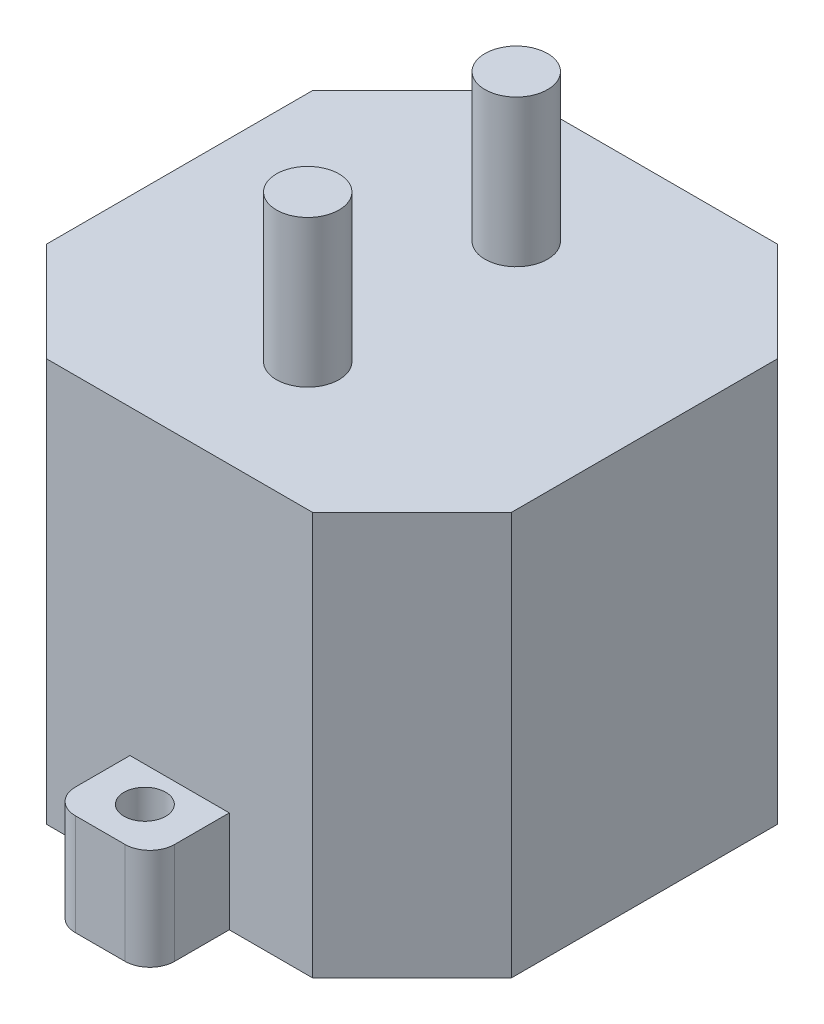
SolidWorks part; units mm, degrees
ref_plane "Front Plane" through (0, 0, 0) normal (0, 0, 1) x (1, 0, 0)
ref_plane "Top Plane" through (0, 0, 0) normal (0, 1, 0) x (1, 0, 0)
ref_plane "Right Plane" through (0, 0, 0) normal (1, 0, 0) x (0, 0, -1)
sketch "Sketch1" plane through (0, 0, 0) normal (0, 1, 0) x (1, 0, 0)
  line L0 (29.718, 59.436) -> (29.718, 0) construction
  line L1 (12.7, 0) -> (46.736, 0)
  line L2 (0, 12.7) -> (0, 46.736)
  line L3 (12.7, 59.436) -> (46.736, 59.436)
  line L4 (59.436, 12.7) -> (59.436, 46.736)
  line L5 (23.368, 0) -> (36.068, 0)
  line L6 (23.368, 0) -> (23.368, -10.16)
  line L7 (23.368, -10.16) -> (36.068, -10.16)
  line L8 (36.068, 0) -> (36.068, -10.16)
  line L9 (23.368, 59.436) -> (36.068, 59.436)
  line L10 (23.368, 59.436) -> (23.368, 69.596)
  line L11 (23.368, 69.596) -> (36.068, 69.596)
  line L12 (36.068, 59.436) -> (36.068, 69.596)
  line L13 (0, 46.736) -> (12.7, 59.436)
  line L14 (0, 12.7) -> (12.7, 0)
  line L15 (46.736, 0) -> (59.436, 12.7)
  line L16 (46.736, 59.436) -> (59.436, 46.736)
  point P0 (0, 0)
  point P1 (59.436, 59.436)
  point P2 (0, 59.436)
  point P3 (59.436, 0)
  point P15 (29.718, 69.596)
  point P16 (29.718, -10.16)
  point P25 (29.718, 59.436)
  dimension "D1" = 59.436
  dimension "D2" = 59.436
  dimension "D3" = 10.16
  dimension "D4" = 12.7
  dimension "D5" = 10.16
  dimension "D6" = 12.7
extrude "Boss-Extrude1" add sketch "Sketch1" along normal blind 12.954 contours L8 L5 L1 L6 L7 | L9 L0 L5 L1 L15 L4 L16 L3 | L0 L3 L13 L2 L14 L1 | L3 L9 L12 L11 L10
sketch "Sketch2" plane through (0, 12.954, 0) normal (0, 1, 0) x (1, 0, 0)
  line L0 (23.368, 59.436) -> (36.068, 59.436)
  line L1 (23.368, 0) -> (36.068, 0)
  line L16 (46.736, 59.436) -> (36.068, 59.436)
  line L17 (36.068, 59.436) -> (36.068, 69.596)
  line L18 (36.068, 69.596) -> (23.368, 69.596)
  line L19 (23.368, 69.596) -> (23.368, 59.436)
  line L20 (23.368, 59.436) -> (12.7, 59.436)
  line L21 (12.7, 59.436) -> (0, 46.736)
  line L22 (0, 46.736) -> (0, 12.7)
  line L23 (0, 12.7) -> (12.7, 0)
  line L24 (12.7, 0) -> (23.368, 0)
  line L25 (23.368, 0) -> (23.368, -10.16)
  line L26 (23.368, -10.16) -> (36.068, -10.16)
  line L27 (36.068, -10.16) -> (36.068, 0)
  line L28 (36.068, 0) -> (46.736, 0)
  line L29 (46.736, 0) -> (59.436, 12.7)
  line L30 (59.436, 12.7) -> (59.436, 46.736)
  line L31 (59.436, 46.736) -> (46.736, 59.436)
  line L32 (46.736, 59.436) -> (36.068, 59.436)
  line L36 (23.368, 59.436) -> (12.7, 59.436)
  line L37 (12.7, 59.436) -> (0, 46.736)
  line L38 (0, 46.736) -> (0, 12.7)
  line L39 (0, 12.7) -> (12.7, 0)
  line L40 (12.7, 0) -> (23.368, 0)
  line L44 (36.068, 0) -> (46.736, 0)
  line L45 (46.736, 0) -> (59.436, 12.7)
  line L46 (59.436, 12.7) -> (59.436, 46.736)
  line L47 (59.436, 46.736) -> (46.736, 59.436)
  dimension "D1" = 0
extrude "Boss-Extrude2" add sketch "Sketch2" along normal blind 38.608
sketch "Sketch3" plane through (0, 12.954, 0) normal (0, 1, 0) x (1, 0, 0)
  line L0 (29.718, 69.596) -> (29.718, -10.16) construction
  line L1 (23.368, 69.596) -> (36.068, 69.596) construction
  line L2 (23.368, -10.16) -> (36.068, -10.16) construction
  circle A0 centre (29.718, 63.881) radius 2.667
  circle A1 centre (29.718, -4.445) radius 2.667
  point P10 (29.718, 29.718)
  dimension "D1" = 5.334
  dimension "D2" = 5.334
  dimension "D3" = 34.163
  dimension "D4" = 34.163
extrude "Cut-Extrude1" cut sketch "Sketch3" against normal through all
fillet "Fillet1" radius 3.175 4 edges at (36.068, 6.477, -69.596) (23.368, 6.477, -69.596) (36.068, 6.477, 10.16) (23.368, 6.477, 10.16)
sketch "Sketch4" plane through (0, 51.562, 0) normal (0, 1, 0) x (1, 0, 0)
  line L0 (29.718, 59.436) -> (29.718, 0) construction
  line L1 (46.736, 59.436) -> (12.7, 59.436) construction
  line L2 (12.7, 0) -> (46.736, 0) construction
  circle A0 centre (29.718, 43.053) radius 4
  circle A1 centre (29.718, 16.383) radius 4
  point P10 (29.718, 29.718)
  dimension "D1" = 8
  dimension "D2" = 8
  dimension "D3" = 13.335
  dimension "D4" = 13.335
extrude "Boss-Extrude3" add sketch "Sketch4" along normal blind 18.796
